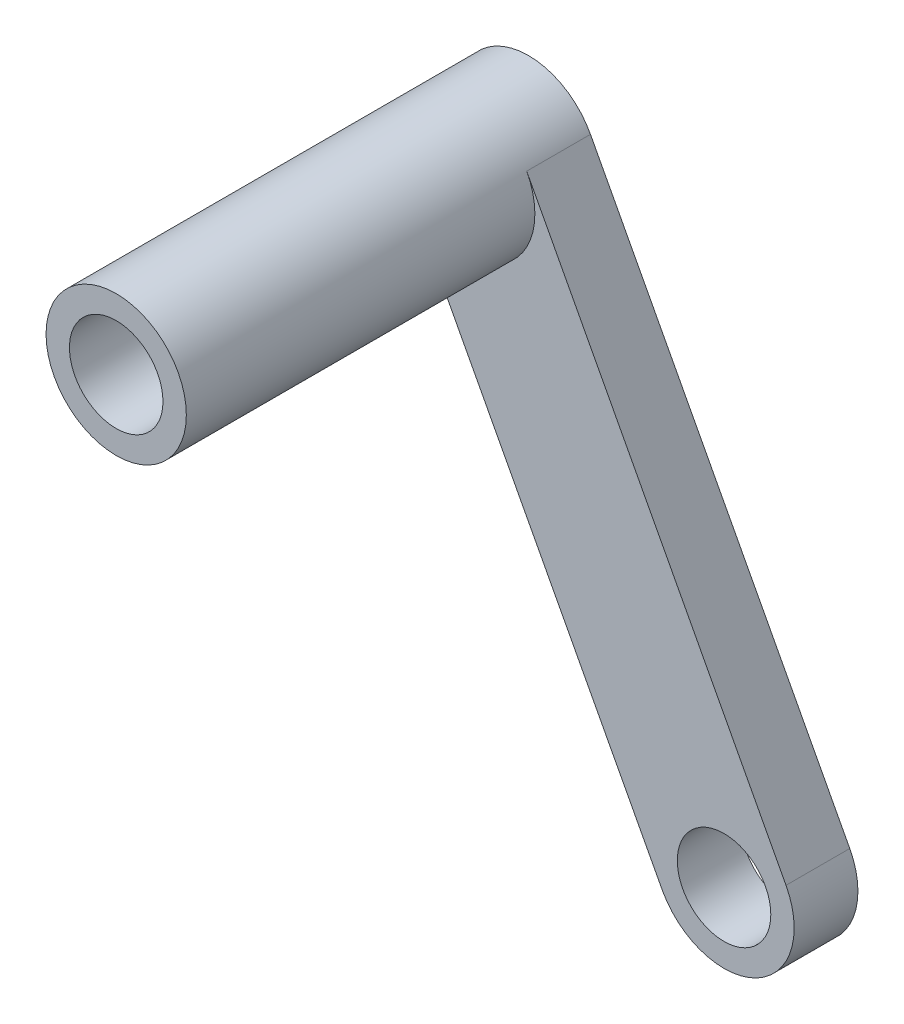
SolidWorks part; units mm, degrees
ref_plane "Front Plane" through (0, 0, 0) normal (0, 0, 1) x (1, 0, 0)
ref_plane "Top Plane" through (0, 0, 0) normal (0, 1, 0) x (1, 0, 0)
ref_plane "Right Plane" through (0, 0, 0) normal (1, 0, 0) x (0, 0, -1)
sketch "Sketch1" plane through (0, 0, 0) normal (0, 0, 1) x (-1, 0, 0)
  line L0 (23.9377, 5.8098) -> (36.1377, -17.1902) construction
  line L1 (26.853, 7.3562) -> (39.053, -15.6438)
  line L2 (21.0224, 4.2635) -> (33.2224, -18.7365)
  arc A0 (26.853, 7.3562) -> (21.0224, 4.2635) centre (23.9377, 5.8098) ccw
  arc A1 (33.2224, -18.7365) -> (39.053, -15.6438) centre (36.1377, -17.1902) ccw
  circle A2 centre (23.9377, 5.8098) radius 2.2
  circle A3 centre (36.1377, -17.1902) radius 2.2
  point P4 (30.0377, -5.6902)
  dimension "D1" = 3.3
extrude "Boss-Extrude1" add sketch "Sketch1" along normal blind 3
sketch "Sketch2" plane through (0, 0, 3) normal (0, 0, 1) x (1, 0, 0)
  circle A0 centre (-36.1377, 17.1902) radius 2.2
  circle A1 centre (-36.1377, 17.1902) radius 3.3
extrude "Boss-Extrude2" add sketch "Sketch2" along normal blind 16.4
